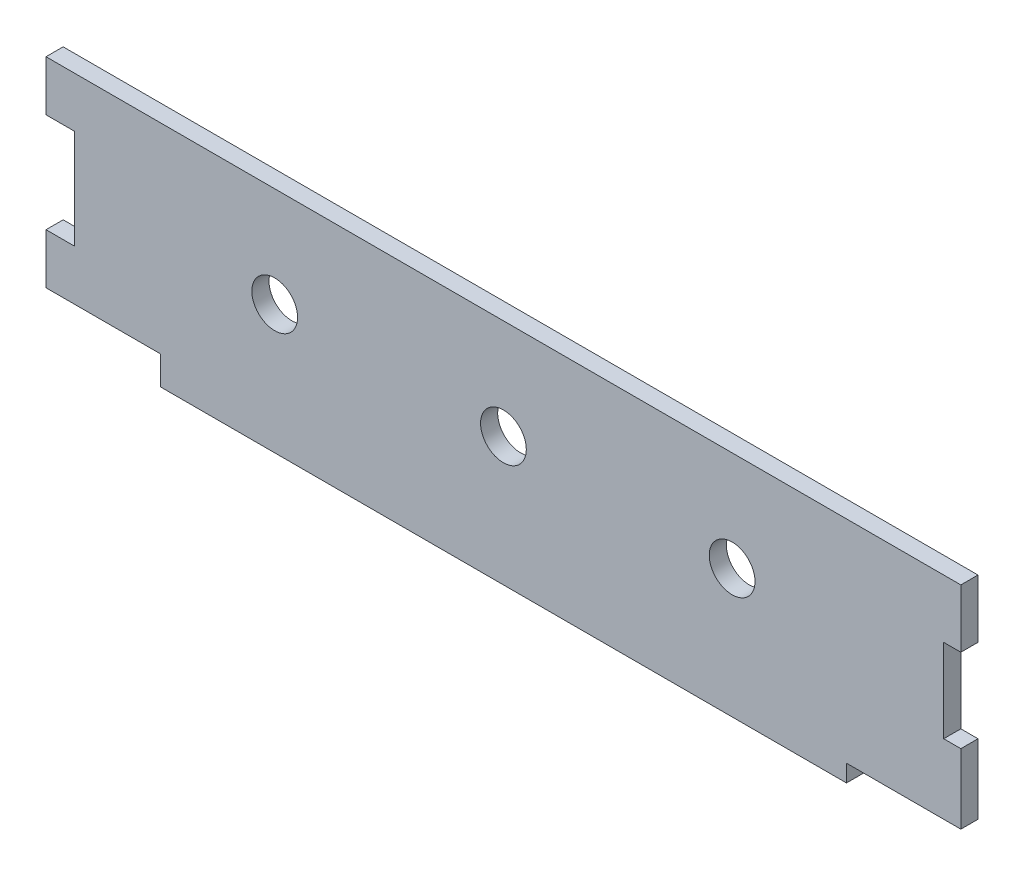
SolidWorks part; units mm, degrees
ref_plane "Alzado" through (0, 0, 0) normal (0, 0, 1) x (1, 0, 0)
ref_plane "Planta" through (0, 0, 0) normal (0, 1, 0) x (1, 0, 0)
ref_plane "Vista lateral" through (0, 0, 0) normal (1, 0, 0) x (0, 0, -1)
sketch "Croquis1" plane through (0, 0, 0) normal (0, 0, 1) x (1, 0, 0)
  line L0 (-40, 8.75) -> (40, 8.75)
  line L1 (40, 8.75) -> (40, 3.65)
  line L2 (40, 3.65) -> (38.5, 3.65)
  line L3 (38.5, 3.65) -> (38.5, -3.65)
  line L4 (38.5, -3.65) -> (40, -3.65)
  line L5 (40, -3.65) -> (40, -9.75)
  line L6 (40, -9.75) -> (30, -9.75)
  line L7 (30, -9.75) -> (30, -11.25)
  line L8 (30, -11.25) -> (-30, -11.25)
  line L9 (-30, -11.25) -> (-30, -8.75)
  line L10 (-30, -8.75) -> (-40, -8.75)
  line L11 (-40, -8.75) -> (-40, -4.35)
  line L12 (-40, -4.35) -> (-37.5, -4.35)
  line L13 (-37.5, -4.35) -> (-37.5, 4.35)
  line L14 (-37.5, 4.35) -> (-40, 4.35)
  line L15 (-40, 4.35) -> (-40, 8.75)
  line L16 (38.5, 0) -> (-37.5, 0) construction
  circle A0 centre (20, 0) radius 2
  circle A1 centre (0, 0) radius 2
  circle A2 centre (-20, 0) radius 2
  point P16 (-37.5, 0)
  point P18 (38.5, 0)
  point P19 (0, 8.75)
  dimension "D9" = 4
  dimension "D10" = 20
  dimension "D11" = 20
  dimension "D12" = 20
  dimension "D1" = 80
  dimension "D2" = 10
  dimension "D3" = 10
  dimension "D4" = 20
  dimension "D5" = 8.7
  dimension "D6" = 7.3
  dimension "D7" = 2.5
  dimension "D8" = 1.5
extrude "Saliente-Extruir1" add sketch "Croquis1" along normal blind 1.5
